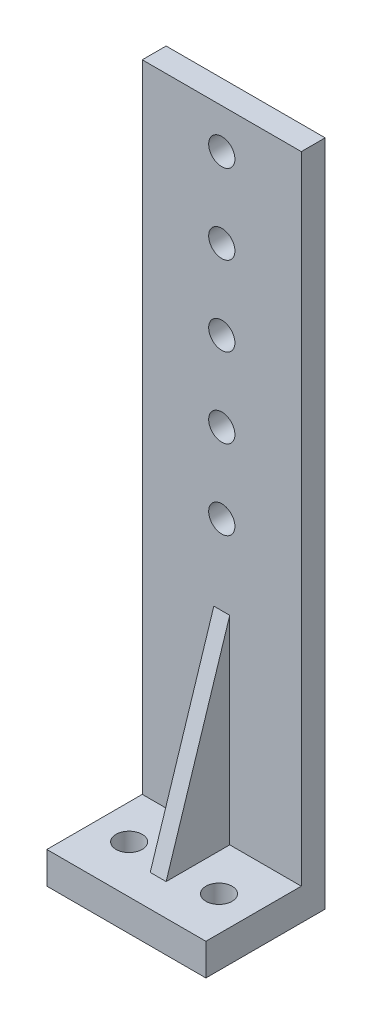
SolidWorks part; units mm, degrees
ref_plane "前视基准面" through (0, 0, 0) normal (0, 0, 1) x (1, 0, 0)
ref_plane "上视基准面" through (0, 0, 0) normal (0, 1, 0) x (1, 0, 0)
ref_plane "右视基准面" through (0, 0, 0) normal (1, 0, 0) x (0, 0, -1)
sketch "草图1" plane through (0, 0, 0) normal (0, 1, 0) x (1, 0, 0)
  line L1 (10, -6) -> (-10, -6)
  line L2 (10, -6) -> (10, 6)
  line L3 (10, 6) -> (-10, 6)
  line L4 (-10, -6) -> (-10, 6)
  line L5 (10, -6) -> (-10, 6) construction
  line L6 (10, 6) -> (-10, -6) construction
  circle A0 centre (-5.65, 0) radius 1.65
  circle A1 centre (5.65, 0) radius 1.65
  point P0 (0, 0)
  dimension "D3" = 3.3
  dimension "D4" = 3.3
  dimension "D5" = 6
  dimension "D6" = 6
  dimension "D7" = 4.35
  dimension "D8" = 4.35
  dimension "D1" = 20
  dimension "D2" = 12
extrude "凸台-拉伸1" add sketch "草图1" along normal blind 4
sketch "草图2" plane through (0, 0, 0) normal (0, 1, 0) x (1, 0, 0)
  line L1 (-10, 6) -> (10, 6)
  line L2 (-10, 6) -> (-10, 9)
  line L3 (-10, 9) -> (10, 9)
  line L4 (10, 6) -> (10, 9)
  dimension "D1" = 3
  dimension "D2" = 20
extrude "凸台-拉伸2" add sketch "草图2" along normal blind 84
sketch "草图3" plane through (0, 0, 0) normal (1, 0, 0) x (0, 0, -1)
  line L0 (-2, 4) -> (6, 4)
  line L1 (6, 4) -> (6, 29)
  line L2 (6, 29) -> (-2, 4)
  dimension "D1" = 8
  dimension "D2" = 2
  dimension "D3" = 4
  dimension "D4" = 25
extrude "凸台-拉伸3" add sketch "草图3" along normal blind 1 and the other way blind 1
sketch "草图4" plane through (0, 0, -6) normal (0, 0, 1) x (1, 0, 0)
  line L4 (-1, 4) -> (1, 4) construction
  circle A0 centre (0, 39) radius 1.65
  circle A1 centre (0, 49) radius 1.65
  circle A2 centre (0, 59) radius 1.65
  circle A3 centre (0, 69) radius 1.65
  circle A4 centre (0, 79) radius 1.65
  dimension "D1" = 3.3
  dimension "D2" = 35
  dimension "D3" = 10
  dimension "D4" = 10
  dimension "D5" = 10
  dimension "D6" = 10
  dimension "D7" = 3.3
  dimension "D8" = 3.3
  dimension "D9" = 3.3
  dimension "D10" = 3.3
extrude "切除-拉伸1" cut sketch "草图4" against normal up to surface (3 mm away) up to face at (0, 42, -9)
